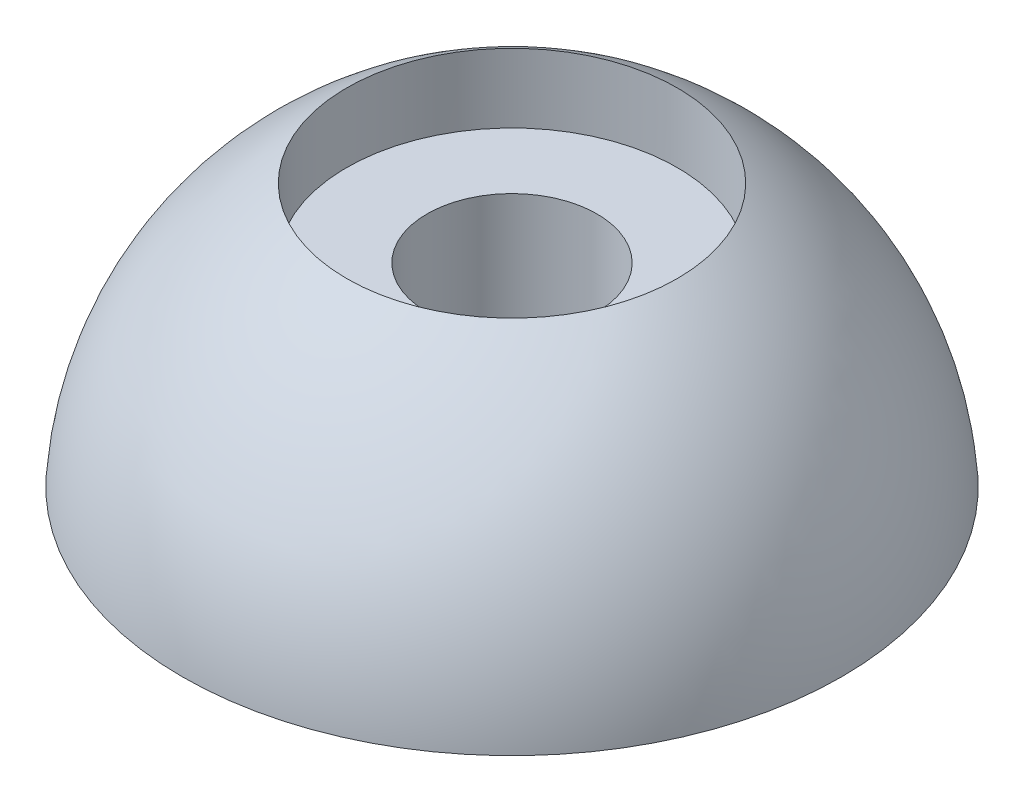
SolidWorks part; units mm, degrees
ref_plane "Front Plane" through (0, 0, 0) normal (0, 0, 1) x (1, 0, 0)
ref_plane "Top Plane" through (0, 0, 0) normal (0, 1, 0) x (1, 0, 0)
ref_plane "Right Plane" through (0, 0, 0) normal (1, 0, 0) x (0, 0, -1)
ref_axis "Axis1" through (0, 58.2777, 0) along (0, -1, 0)
sketch "Sketch1" plane through (0, 0, 0) normal (0, 0, 1) x (1, 0, 0)
  line L0 (0, 0) -> (0, 6.5)
  line L1 (0, 0) -> (6.9821, 0)
  line L2 (-0.8575, 6.5) -> (7582.5995, 6.5) construction
  arc A0 (0, 6.5) -> (6.9821, 0) centre (0, -0.5) cw
  dimension "D1" = 7
revolve "Revolve1" add sketch "Sketch1" angle 360 about axis through (0, 58.2777, 0) along (0, -1, 0)
sketch "Sketch2" plane through (0, 0, 0) normal (0, -1, 0) x (1, 0, 0)
  circle A0 centre (0, 0) radius 1.5
  dimension "D1" = 3
ref_plane "Plane1" through (0, 6.5, 0) normal (0, 1, 0) x (1, 0, 0)
hole_wizard "CBORE for M3 Pan Head Screw1" positions "Sketch4" profile "Sketch3" counterbore size "M3" standard "ISO" end condition through all
sketch "Sketch4" plane through (0, 6.5, 0) normal (0, 1, 0) x (1, 0, 0)
  point P0 (0, 0)
sketch "Sketch3" plane through (0, 6.5, 0) normal (1, 0, 0) x (0, 0, 1)
  line L0 (0, 0) -> (0, 6.5)
  line L1 (0, 6.5) -> (1.8, 6.5)
  line L3 (1.8, 6.5) -> (1.8, 2.4)
  line L4 (1.8, 2.4) -> (3.5, 2.4)
  line L5 (3.5, 2.4) -> (3.5, 0)
  line L7 (3.5, 0) -> (0, 0)
  line L11 (0, -6.35) -> (0, 107.95) construction
  dimension "Thru Hole Dia." = 3.6
  dimension "Thru Hole Depth" = 6.5
  dimension "C'Bore Dia." = 7
  dimension "C'Bore Depth" = 2.4
